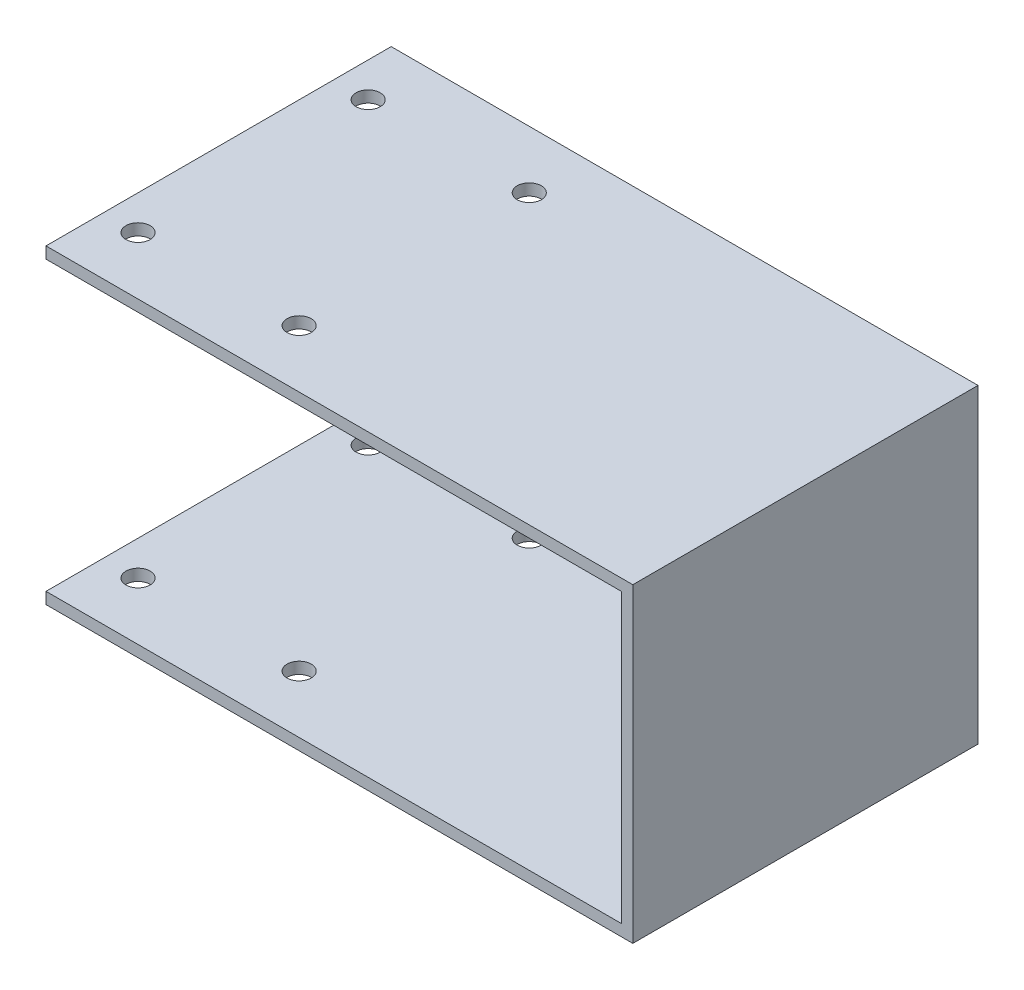
SolidWorks part; units mm, degrees
ref_plane "前视基准面" through (0, 0, 0) normal (0, 0, 1) x (1, 0, 0)
ref_plane "上视基准面" through (0, 0, 0) normal (0, 1, 0) x (1, 0, 0)
ref_plane "右视基准面" through (0, 0, 0) normal (1, 0, 0) x (0, 0, -1)
other "Configuration Table"
sketch "草图1" plane through (0, 0, 0) normal (0, 0, 1) x (1, 0, 0)
  line L0 (0, 0) -> (0, 2)
  line L1 (0, 2) -> (102, 2)
  line L2 (102, 2) -> (102, -52)
  line L3 (102, -52) -> (0, -52)
  line L4 (0, -52) -> (0, -50)
  line L5 (0, -50) -> (100, -50)
  line L6 (100, -50) -> (100, 0)
  line L7 (100, 0) -> (0, 0)
  dimension "D1" = 2
  dimension "D2" = 100
  dimension "D3" = 2
  dimension "D4" = 2
  dimension "D5" = 50
extrude "凸台-拉伸1" add sketch "草图1" along normal blind 60 contours L5 L6 L7 L0 L1 L2 L3 L4
sketch "Sketch1" plane through (0, 0, 0) normal (0, 1, 0) x (1, 0, 0)
  line L0 (0, -60) -> (0, 0) construction
  line L1 (6, -10) -> (34, -10) construction
  line L2 (6, -10) -> (6, -50) construction
  line L3 (6, -50) -> (34, -50) construction
  line L4 (34, -10) -> (34, -50) construction
  line L5 (0, 0) -> (102, -60) construction
  line L6 (102, 0) -> (0, -60) construction
  line L7 (51, -30) -> (87.6415, -30) construction
  line L8 (0, 0) -> (102, 0) construction
  circle A0 centre (6, -10) radius 2.1
  circle A1 centre (34, -10) radius 2.1
  circle A2 centre (34, -50) radius 2.1
  circle A3 centre (6, -50) radius 2.1
  point P18 (51, -30)
  dimension "D5" = 4.2
  dimension "D6" = 4.2
  dimension "D7" = 4.2
  dimension "D8" = 4.2
  dimension "D1" = 6
  dimension "D2" = 28
  dimension "D3" = 40
  dimension "D4" = 20
extrude "Cut-Extrude1" cut sketch "Sketch1" along normal through all both and the other way through all
